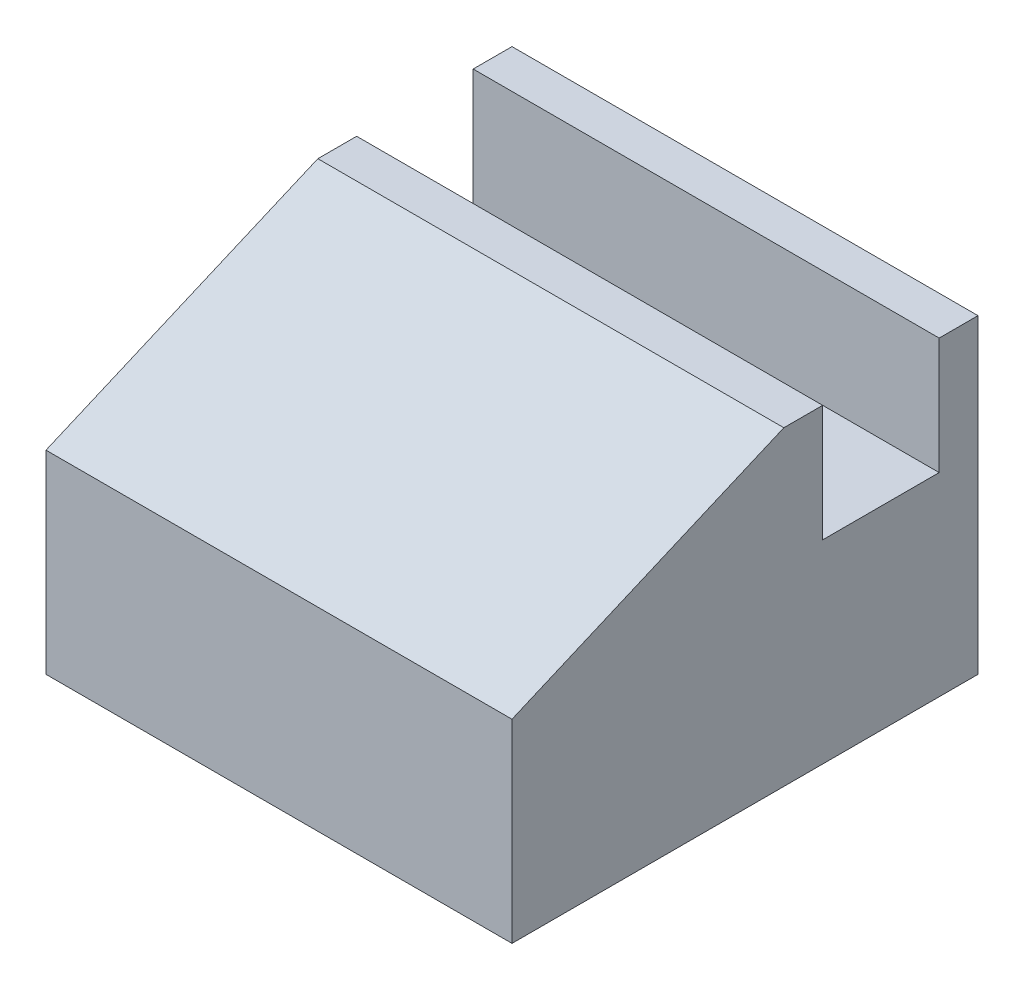
SolidWorks part; units mm, degrees
ref_plane "Front Plane" through (0, 0, 0) normal (0, 0, 1) x (1, 0, 0)
ref_plane "Top Plane" through (0, 0, 0) normal (0, 1, 0) x (1, 0, 0)
ref_plane "Right Plane" through (0, 0, 0) normal (1, 0, 0) x (0, 0, -1)
sketch "Main" plane through (0, 0, 0) normal (1, 0, 0) x (0, 0, -1)
  line L0 (-76.2, -50.8) -> (-76.2, -19.05)
  line L2 (-76.2, -19.05) -> (-31.75, 0)
  line L3 (-31.75, 0) -> (-25.4, 0)
  line L4 (-25.4, 0) -> (-25.4, -19.05)
  line L5 (-25.4, -19.05) -> (-6.35, -19.05)
  line L6 (-6.35, -19.05) -> (-6.35, 0)
  line L7 (-6.35, 0) -> (0, 0)
  line L8 (0, 0) -> (0, -50.8)
  line L10 (0, -50.8) -> (-76.2, -50.8)
  dimension "D1" = 31.75
  dimension "D2" = 50.8
  dimension "D3" = 69.85
  dimension "D4" = 50.8
  dimension "D5" = 76.2
  dimension "D6" = 50.8
  dimension "D7" = 44.45
  dimension "D8" = 31.75
extrude "Card" add sketch "Main" along normal blind 76.2
sketch "OSU" plane through (0, 11.4957, 4.9267) normal (0, 0.9191, 0.3939) x (1, 0, 0)
  line L0 (38.1, -29.1829) -> (38.1, -77.543) construction
  line L1 (76.2, -29.1829) -> (0, -29.1829) construction
  line L2 (76.2, -77.543) -> (0, -77.543) construction
  line L3 (30.988, -53.3629) -> (45.212, -53.3629) construction
  line L6 (30.988, -65.2501) -> (30.988, -41.4757)
  line L7 (30.988, -41.4757) -> (33.274, -39.1897)
  line L8 (33.274, -39.1897) -> (42.926, -39.1897)
  line L9 (42.926, -39.1897) -> (45.212, -41.4757)
  line L10 (45.212, -41.4757) -> (45.212, -65.2501)
  line L11 (45.212, -65.2501) -> (42.926, -67.5361)
  line L12 (42.926, -67.5361) -> (33.274, -67.5361)
  line L13 (33.274, -67.5361) -> (30.988, -65.2501)
  line L14 (45.212, -32.3317) -> (51.816, -39.1897)
  line L15 (51.816, -39.1897) -> (51.816, -67.5361)
  line L16 (51.816, -67.5361) -> (45.212, -74.3941)
  line L17 (45.212, -74.3941) -> (30.988, -74.3941)
  line L18 (30.988, -74.3941) -> (24.384, -67.5361)
  line L19 (24.384, -67.5361) -> (24.384, -39.1897)
  line L20 (24.384, -39.1897) -> (30.988, -32.3317)
  line L21 (30.988, -32.3317) -> (45.212, -32.3317)
  point P8 (38.1, -53.3629)
  point P9 (38.1, -53.3629)
  dimension "D1" = 42.0624
  dimension "D2" = 35.2044
  dimension "D3" = 9.144
  dimension "D4" = 32.9184
  dimension "D5" = 8.89
  dimension "D6" = 18.542
  dimension "D7" = 6.858
  dimension "D8" = 6.604
  dimension "D9" = 27.432
  dimension "D10" = 20.828
extrude "Engraving" [suppressed] cut sketch "OSU" against normal blind 1.27
